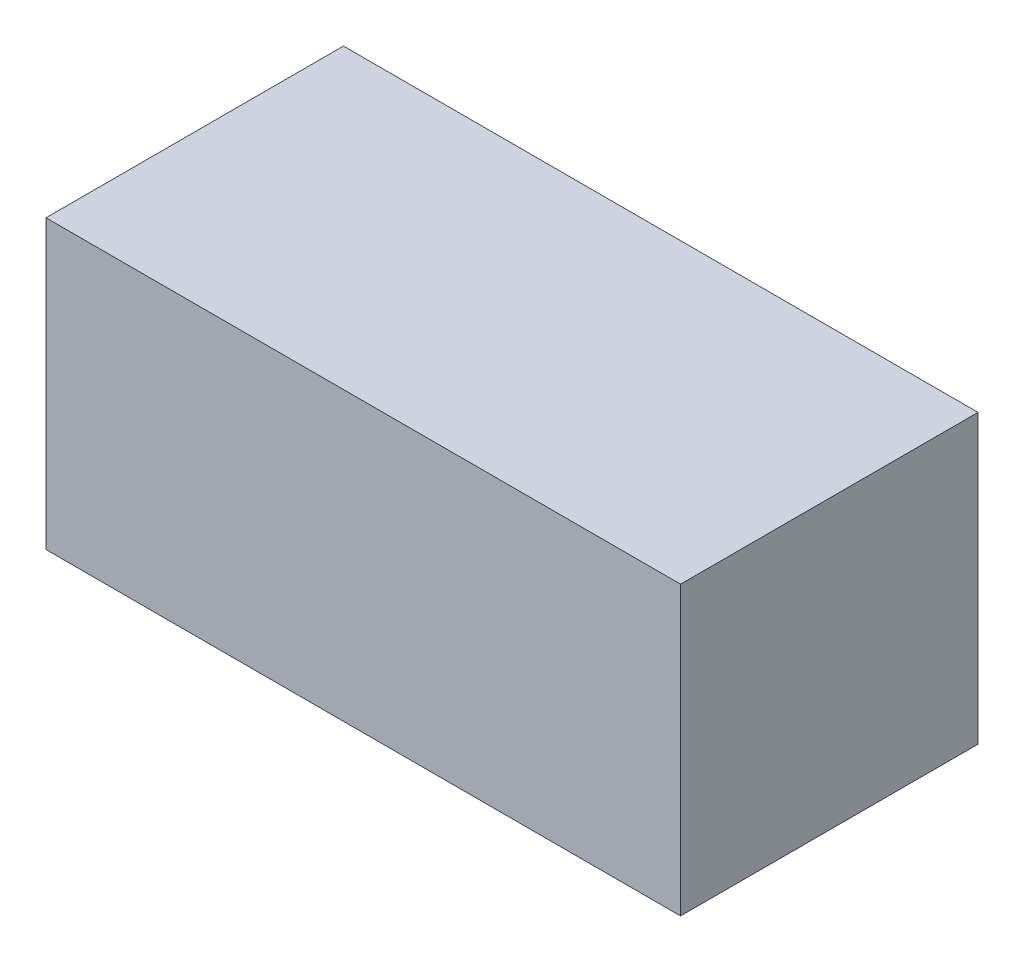
SolidWorks part; units mm, degrees
ref_plane "Front Plane" through (0, 0, 0) normal (0, 0, 1) x (1, 0, 0)
ref_plane "Top Plane" through (0, 0, 0) normal (0, 1, 0) x (1, 0, 0)
ref_plane "Right Plane" through (0, 0, 0) normal (1, 0, 0) x (0, 0, -1)
sketch "Sketch1" plane through (0, 0, 0) normal (0, 0, 1) x (1, 0, 0)
  line L0 (-1.0666, 0.483) -> (1.0666, 0.483)
  line L1 (1.0666, 0.483) -> (1.0666, -0.483)
  line L2 (1.0666, -0.483) -> (-1.0666, -0.483)
  line L3 (-1.0666, -0.483) -> (-1.0666, 0.483)
extrude "Component_Outline" add sketch "Sketch1" along normal blind 1 separate body
sketch3d "3DSketch1"
  line L0 (0, 0, 0) -> (1, 0, 0)
  line L1 (0, 0, 0) -> (0, 1, 0)
  line L2 (0, 0, 0) -> (0, 0, 1)
  point P0 (0, 0, 0)
